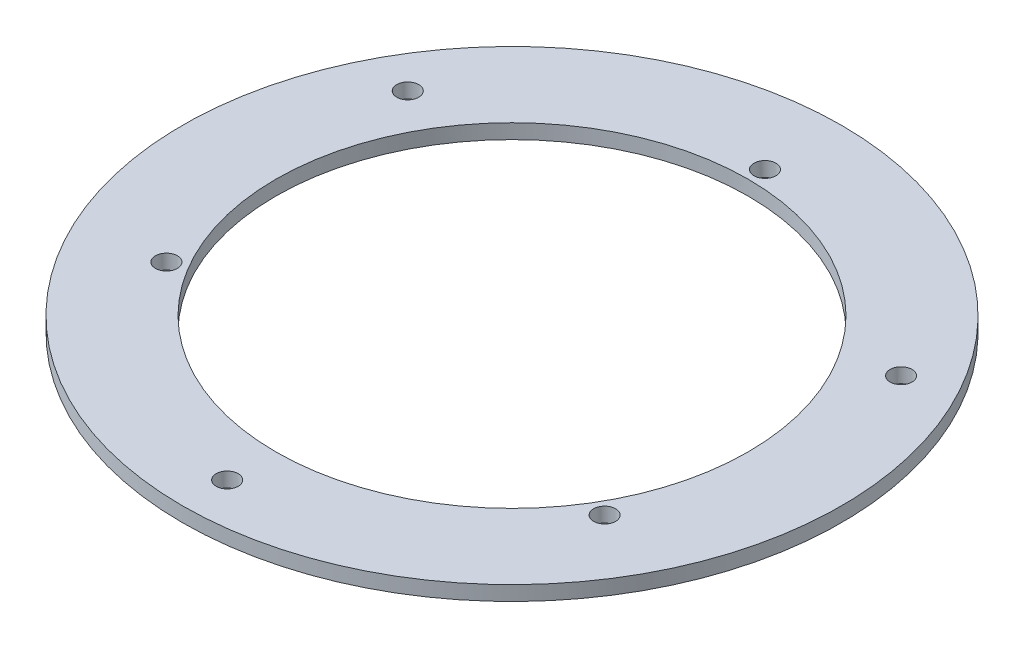
SolidWorks part; units mm, degrees
ref_plane "Front Plane" through (0, 0, 0) normal (0, 0, 1) x (1, 0, 0)
ref_plane "Top Plane" through (0, 0, 0) normal (0, 1, 0) x (1, 0, 0)
ref_plane "Right Plane" through (0, 0, 0) normal (1, 0, 0) x (0, 0, -1)
sketch "Sketch2" plane through (0, 0, 0) normal (0, 1, 0) x (1, 0, 0)
  line L0 (0, 34.5439) -> (-29.9159, -17.2719) construction
  line L1 (-29.9159, -17.2719) -> (29.9159, -17.2719) construction
  line L2 (29.9159, -17.2719) -> (0, 34.5439) construction
  line L3 (0, 34.5439) -> (0, -17.2719) construction
  line L4 (-29.9159, -17.2719) -> (14.9579, 8.636) construction
  line L5 (33.6803, 19.4454) -> (-33.6803, 19.4453) construction
  line L6 (-33.6803, 19.4453) -> (0, -38.8907) construction
  line L7 (0, -38.8907) -> (33.6803, 19.4454) construction
  line L8 (33.6803, 19.4454) -> (-16.8402, -9.7227) construction
  line L9 (-33.6803, 19.4453) -> (16.8402, -9.7227) construction
  circle A0 centre (0, 34.5439) radius 1.5
  circle A1 centre (-29.9159, -17.2719) radius 1.5
  circle A2 centre (29.9159, -17.2719) radius 1.5
  circle A3 centre (33.6803, 19.4454) radius 1.5
  circle A4 centre (-33.6803, 19.4453) radius 1.5
  circle A5 centre (0, -38.8907) radius 1.5
  circle A6 centre (0, 0) radius 45
  circle A7 centre (0, 0) radius 32.25
  point P6 (0, 0)
  point P16 (0, 0)
  dimension "D1" = 3
  dimension "D3" = 3
  dimension "D6" = 64.5
  dimension "D7" = 90
  dimension "D2" = 34.5439
  dimension "D4" = 38.8907
  dimension "D5" = 60
extrude "Boss-Extrude1" add sketch "Sketch2" along normal blind 2
